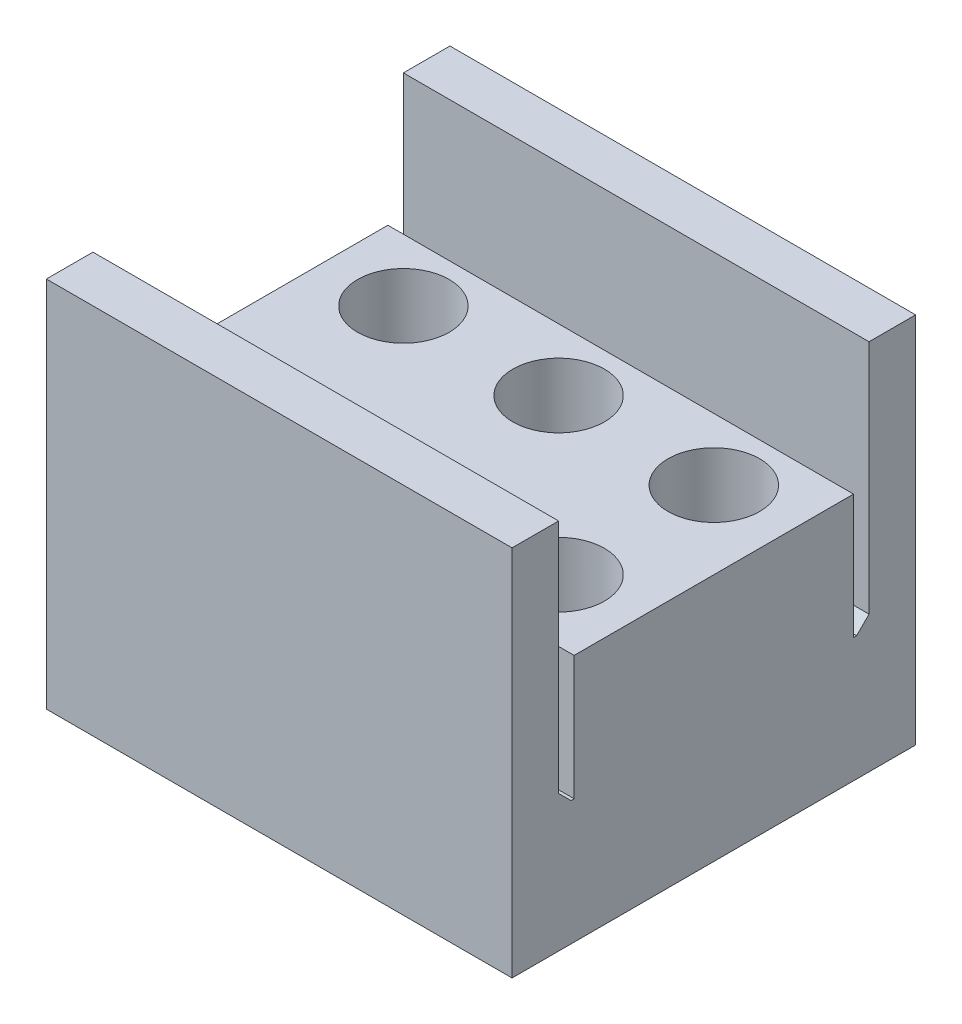
SolidWorks part; units mm, degrees
ref_plane "Front Plane" through (0, 0, 0) normal (0, 0, 1) x (1, 0, 0)
ref_plane "Top Plane" through (0, 0, 0) normal (0, 1, 0) x (1, 0, 0)
ref_plane "Right Plane" through (0, 0, 0) normal (1, 0, 0) x (0, 0, -1)
sketch "Sketch1" plane through (0, 0, 0) normal (0, 1, 0) x (1, 0, 0)
  line L1 (-7.5, 6.5) -> (7.5, 6.5)
  line L2 (-7.5, 6.5) -> (-7.5, -6.5)
  line L3 (-7.5, -6.5) -> (7.5, -6.5)
  line L4 (7.5, 6.5) -> (7.5, -6.5)
  line L5 (-7.5, 6.5) -> (7.5, -6.5) construction
  line L6 (-7.5, -6.5) -> (7.5, 6.5) construction
  point P0 (0, 0)
  dimension "D1" = 15
  dimension "D2" = 13
extrude "Boss-Extrude1" add sketch "Sketch1" along normal blind 8
sketch "Sketch8" plane through (0, 8, 0) normal (0, 1, 0) x (1, 0, 0)
  line L0 (7.5, -6.5) -> (7.5, 6.5) construction
  line L1 (-7.5, 6.5) -> (7.5, 6.5)
  line L2 (-7.5, 6.5) -> (-7.5, 5)
  line L3 (-7.5, 5) -> (7.5, 5)
  line L4 (7.5, 6.5) -> (7.5, 5)
  line L6 (-7.5, -6.5) -> (7.5, -6.5)
  line L7 (-7.5, -6.5) -> (-7.5, -5)
  line L8 (-7.5, -5) -> (7.5, -5)
  line L9 (7.5, -6.5) -> (7.5, -5)
  dimension "D1" = 10
extrude "Boss-Extrude4" add sketch "Sketch8" along normal blind 4
sketch "Sketch9" plane through (0, 8, 0) normal (0, 1, 0) x (1, 0, 0)
  line L0 (7.5, -5) -> (7.5, 5) construction
  line L1 (-7.5, 5) -> (7.5, 5)
  line L2 (-7.5, 5) -> (-7.5, 4.5)
  line L3 (-7.5, 4.5) -> (7.5, 4.5)
  line L4 (7.5, 5) -> (7.5, 4.5)
  line L5 (-7.5, 5) -> (-7.5, -5) construction
  line L6 (-7.5, -5) -> (7.5, -5)
  line L7 (-7.5, -5) -> (-7.5, -4.5)
  line L8 (-7.5, -4.5) -> (7.5, -4.5)
  line L9 (7.5, -5) -> (7.5, -4.5)
  line L10 (7.5, -5) -> (-7.5, -5) construction
  dimension "D1" = 0.5
extrude "Cut-Extrude3" cut sketch "Sketch9" against normal blind 4
chamfer "Chamfer1" distance 0.4 angle 45 2 edges at (0, 4, 5) (0, 4, -5)
sketch "Sketch4" plane through (0, 0, 0) normal (0, -1, 0) x (1, 0, 0)
  circle A0 centre (-5, 2.5) radius 1.475
  point P2 (-5, 1.5086)
  dimension "D1" = 2.95
  dimension "D2" = 2.5
  dimension "D3" = 5
extrude "Cut-Extrude2" cut sketch "Sketch4" against normal up to surface (8 mm away) up to face at (0, 8, 0)
pattern_linear "LPattern1" count 3 spacing 5 along (1, 0, 0) count 2 spacing 5 along (0, 0, -1) of "Cut-Extrude2"
